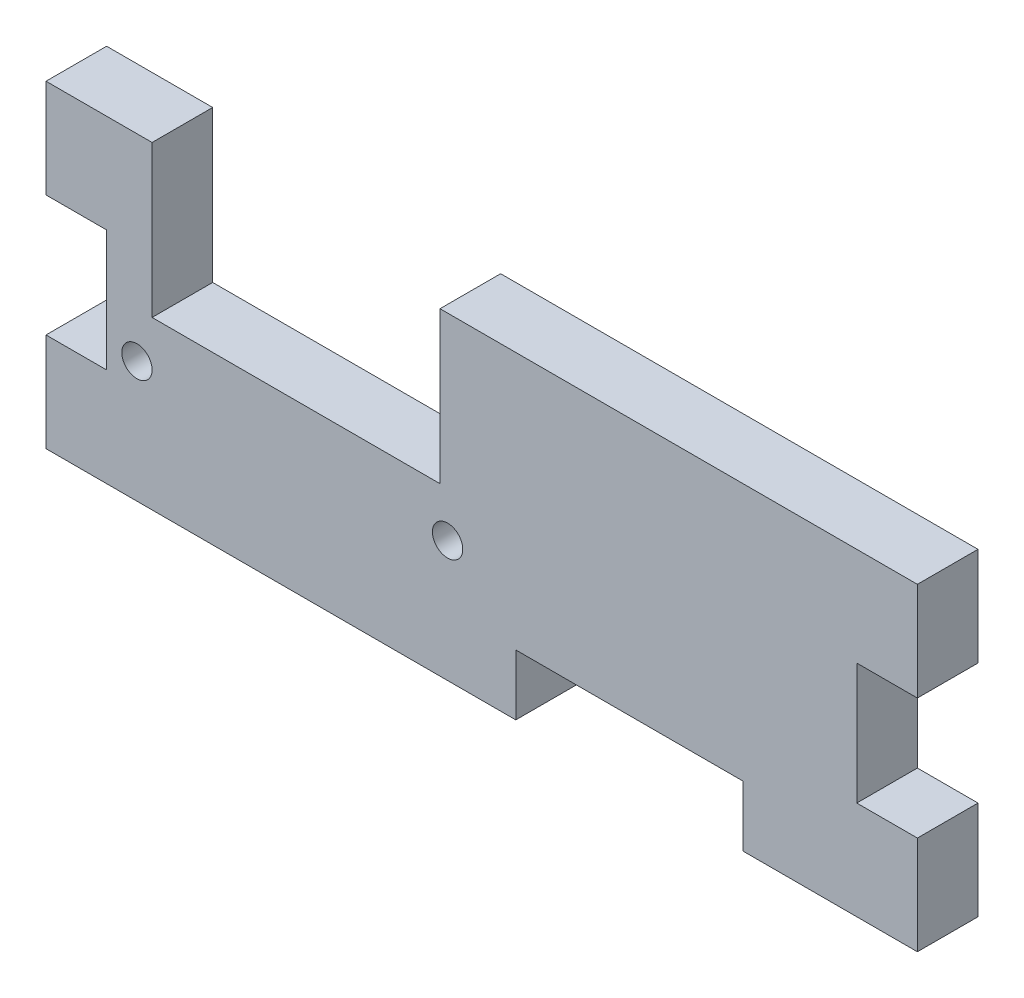
SolidWorks part; units mm, degrees
ref_plane "Спереди" through (0, 0, 0) normal (0, 0, 1) x (1, 0, 0)
ref_plane "Сверху" through (0, 0, 0) normal (0, 1, 0) x (1, 0, 0)
ref_plane "Справа" through (0, 0, 0) normal (1, 0, 0) x (0, 0, -1)
other "Configuration Table"
sketch "Эскиз1" plane through (0, 0, 0) normal (0, 0, 1) x (1, 0, 0)
  line L0 (12.5, 0) -> (12.5, 15) construction
  line L2 (0, 0) -> (0, 15)
  line L5 (22, 15) -> (49.5, 15)
  line L6 (3, 5) -> (3, 15)
  line L7 (22, 5) -> (22, 15)
  line L10 (0, 0) -> (0, -6)
  line L11 (0, -6) -> (49.5, -6)
  line L12 (49.5, -6) -> (49.5, 15)
  line L14 (3, 5) -> (22, 5)
  line L18 (24.75, 15) -> (24.75, -6) construction
  line L19 (0, 15) -> (3, 15)
  circle A2 centre (22.5, 2) radius 1
  circle A3 centre (2, 2) radius 1
  dimension "D3" = 12.5
  dimension "D2" = 5
  dimension "D4" = 49.5
  dimension "D5" = 20.5
  dimension "D7" = 2
  dimension "D8" = 6
  dimension "D10" = 19
  dimension "D12" = 2
  dimension "D15" = 15
extrude "Бобышка-Вытянуть1" add sketch "Эскиз1" along normal blind 4
sketch "Эскиз2" plane through (0, 0, 4) normal (0, 0, 1) x (1, 0, 0)
  line L1 (24.75, 34.804) -> (24.75, -6) construction
  line L2 (0, -6) -> (49.5, -6) construction
  line L4 (27, -6) -> (42, -6)
  line L5 (27, -6) -> (27, -2)
  line L6 (27, -2) -> (42, -2)
  line L7 (42, -6) -> (42, -2)
  dimension "D1" = 27
  dimension "D2" = 15
  dimension "D3" = 4
extrude "Вырез-Вытянуть1" cut sketch "Эскиз2" against normal blind 10
sketch "Эскиз3" plane through (0, 0, 4) normal (0, 0, 1) x (1, 0, 0)
  line L0 (49.5, -6) -> (49.5, 15) construction
  line L1 (0, -6) -> (-4, -6)
  line L2 (0, -6) -> (0, 0.5)
  line L3 (0, 15) -> (-4, 15)
  line L4 (-4, -6) -> (-4, 0.5)
  line L5 (49.5, 15) -> (53.5, 15)
  line L6 (49.5, 15) -> (49.5, 8.5)
  line L7 (49.5, -6) -> (53.5, -6)
  line L8 (53.5, 15) -> (53.5, 8.5)
  line L9 (-4, 8.5) -> (0, 8.5)
  line L10 (-4, 4.5) -> (53.5, 4.5) construction
  line L11 (-4, 0.5) -> (0, 0.5)
  line L12 (-4, 8.5) -> (-4, 15)
  line L13 (0, 8.5) -> (0, 15)
  line L14 (49.5, 8.5) -> (53.5, 8.5)
  line L15 (49.5, 0.5) -> (53.5, 0.5)
  line L16 (49.5, 0.5) -> (49.5, -6)
  line L17 (53.5, 0.5) -> (53.5, -6)
  dimension "D1" = 21
  dimension "D2" = 4
  dimension "D3" = 21
  dimension "D4" = 4
  dimension "D5" = 8
extrude "Бобышка-Вытянуть2" add sketch "Эскиз3" against normal blind 4
